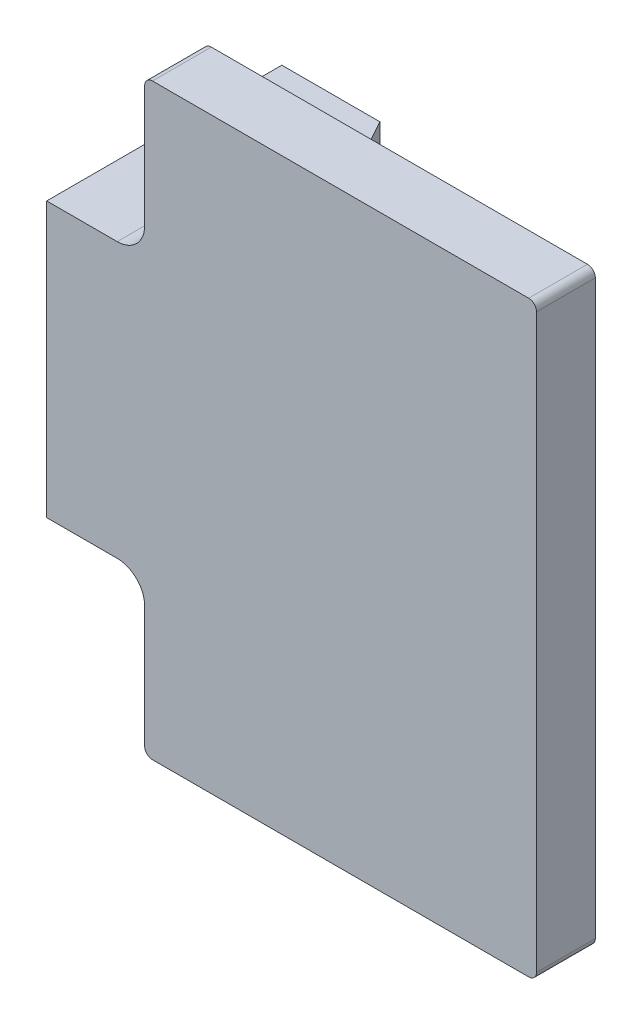
SolidWorks part; units mm, degrees
ref_plane "Plan de face" through (0, 0, 0) normal (0, 0, 1) x (1, 0, 0)
ref_plane "Plan de dessus" through (0, 0, 0) normal (0, 1, 0) x (1, 0, 0)
ref_plane "Plan de droite" through (0, 0, 0) normal (1, 0, 0) x (0, 0, -1)
sketch "Esquisse1" plane through (0, 0, 0) normal (0, 0, 1) x (1, 0, 0)
  line L1 (0, 75) -> (100, 75)
  line L2 (0, 75) -> (0, -75)
  line L3 (0, -75) -> (100, -75)
  line L4 (100, 75) -> (100, -75)
  point P4 (0, 0)
  dimension "D1" = 100
  dimension "D2" = 150
extrude "Boss.-Extru.1" add sketch "Esquisse1" along normal blind 15
sketch "Esquisse2" plane through (0, 0, 15) normal (0, 0, 1) x (1, 0, 0)
  line L0 (0, 75) -> (0, -75) construction
  line L1 (0, 35) -> (-25, 35)
  line L2 (0, 35) -> (0, -35)
  line L3 (0, -35) -> (-25, -35)
  line L4 (-25, 35) -> (-25, -35)
  point P6 (-25, 0)
  dimension "D1" = 70
  dimension "D2" = 25
extrude "Boss.-Extru.2" add sketch "Esquisse2" against normal blind 60
sketch3d "Esquisse3D1"
  line L0 (-25, -35, 5) -> (-25, 35, -45) construction
  line L1 (-25, 35, 5) -> (-25, -35, -45) construction
  line L2 (-25, 0, -20) -> (-55.4382, 0, -20) construction
  line L3 (-25, -35, -45) -> (-25, -35, 15) construction
  line L4 (-25, 35, 15) -> (-25, -35, 15) construction
  dimension "D1" = 10
sketch "Esquisse4" plane through (-25, 0, 0) normal (-1, 0, 0) x (0, 0, 1)
  line L0 (-33.7, 4) -> (-20.2188, 4) construction
  line L1 (-20.2188, -4) -> (-33.7, -4) construction
  line L2 (-33.7, 4) -> (-20.2188, 4) construction
  line L3 (-20.2188, -4) -> (-33.7, -4) construction
  line L4 (-2.2, 0) -> (-2.2, 6.5)
  line L5 (-3.2, 7.5) -> (-9.7, 7.5)
  line L6 (-9.7, -7.5) -> (-15.9939, -7.5)
  line L7 (-16.9939, -6.5) -> (-16.9939, -4.609)
  line L8 (-20.2188, -4.1) -> (-33.7, -4.1)
  line L9 (-33.7, 4.1) -> (-20.2188, 4.1)
  circle A0 centre (-9.7, 0) radius 7.4 construction
  arc A1 (-20.2188, 4) -> (-14.0313, 6) centre (-20.2188, 14.5714) ccw construction
  arc A2 (-14.0313, -6) -> (-20.2188, -4) centre (-20.2188, -14.5714) ccw construction
  arc A3 (-33.7, 4) -> (-37.7, 0) centre (-33.7, 0) ccw construction
  arc A4 (-37.7, 0) -> (-33.7, -4) centre (-33.7, 0) ccw construction
  arc A5 (-14.0313, -6) -> (-14.0313, 6) centre (-9.7, 0) ccw construction
  arc A6 (-20.2188, 4) -> (-14.0313, 6) centre (-20.2188, 14.5714) ccw construction
  arc A7 (-14.0313, -6) -> (-20.2188, -4) centre (-20.2188, -14.5714) ccw construction
  arc A8 (-33.7, 4) -> (-37.7, 0) centre (-33.7, 0) ccw construction
  arc A9 (-37.7, 0) -> (-33.7, -4) centre (-33.7, 0) ccw construction
  arc A10 (-37.8, 0) -> (-33.7, -4.1) centre (-33.7, 0) ccw
  arc A11 (-33.7, 4.1) -> (-37.8, 0) centre (-33.7, 0) ccw
  arc A12 (-20.2188, 4.1) -> (-14.0898, 6.0811) centre (-20.2188, 14.5714) ccw
  arc A13 (-9.7, -7.5) -> (-2.2, 0) centre (-9.7, 0) ccw
  arc A14 (-16.9939, -4.609) -> (-20.2188, -4.1) centre (-20.2188, -14.5714) ccw
  arc A15 (-9.7, 7.5) -> (-14.0898, 6.0811) centre (-9.7, 0) ccw
  arc A16 (-14.0898, -6.0811) -> (-14.0898, 6.0811) centre (-9.7, 0) ccw construction
  arc A17 (-2.2, 6.5) -> (-3.2, 7.5) centre (-3.2, 6.5) ccw
  arc A18 (-14.0898, -6.0811) -> (-20.2188, -4.1) centre (-20.2188, -14.5714) ccw construction
  arc A19 (-15.9939, -7.5) -> (-16.9939, -6.5) centre (-15.9939, -6.5) cw
  dimension "D2" = 1
  dimension "D3" = 0.1
  dimension "D4" = 1
  dimension "D1" = 0.1
extrude "Enlèv. mat.-Extru.1" cut sketch "Esquisse4" against normal blind 4.15
sketch "Esquisse6" plane through (-20.85, 0, 0) normal (-1, 0, 0) x (0, 0, 1)
  line L2 (-29.7, 3) -> (-33.7, 3)
  line L3 (-33.7, -3) -> (-29.7, -3)
  line L12 (-29.7, 3) -> (-33.7, 3) construction
  line L13 (-33.7, -3) -> (-29.7, -3) construction
  circle A0 centre (-33.7, 0) radius 1.75
  arc A1 (-32.45, 0) -> (-34.95, 0) centre (-33.7, 0) ccw construction
  circle A2 centre (-9.7, 0) radius 2.05
  arc A3 (-33.7, 3) -> (-36.7, 0) centre (-33.7, 0) ccw
  arc A4 (-36.7, 0) -> (-33.7, -3) centre (-33.7, 0) ccw
  arc A5 (-29.7, -3) -> (-29.7, 3) centre (-29.7, 0) ccw
  arc A6 (-33.7, 3) -> (-36.7, 0) centre (-33.7, 0) ccw construction
  arc A7 (-36.7, 0) -> (-33.7, -3) centre (-33.7, 0) ccw construction
  arc A8 (-29.7, -3) -> (-29.7, 3) centre (-29.7, 0) ccw construction
  arc A9 (-8.1793, 0.3) -> (-11.2207, 0.3) centre (-9.7, 0) ccw construction
  dimension "D3" = 0.5
  dimension "D4" = 0.5
  dimension "D2" = 0
hole_wizard "Chambrage pour vis à tête ronde bombée M32" positions "Esquisse3D3" profile "Esquisse9" counterbore size "M3" standard "Ansi Metric" end condition up to next
sketch3d "Esquisse3D3"
  point P0 (0, 0, -33.7)
  point P2 (0, 0, -9.7)
sketch "Esquisse9" plane through (0, 0, -33.7) normal (0, 1, 0) x (0, 0, -1)
  line L0 (0, 0) -> (0, 20.85)
  line L1 (0, 20.85) -> (1.7, 20.85)
  line L3 (1.7, 20.85) -> (1.7, 2.4)
  line L4 (1.7, 2.4) -> (3.5, 2.4)
  line L5 (3.5, 2.4) -> (3.5, 0)
  line L7 (3.5, 0) -> (0, 0)
  line L11 (0, -6.35) -> (0, 107.95) construction
  dimension "Diamètre du perçage jusqu'au prochain" = 3.4
  dimension "Profondeur du perçage jusqu'au prochain" = 20.85
  dimension "Diamètre du chambrage" = 7
  dimension "Profondeur du chambrage" = 2.4
sketch "Esquisse10" plane through (0, -35, 0) normal (0, -1, 0) x (1, 0, 0)
  line L0 (0, -45) -> (25, 0)
  line L1 (0, 0) -> (100, 0) construction
  line L2 (25, 0) -> (0, 0)
  line L3 (0, 0) -> (0, -45)
  dimension "D1" = 25
extrude "Boss.-Extru.3" add sketch "Esquisse10" against normal blind 10
mirror "Symétrie1" about plane through (0, 0, 0) normal (0, 1, 0) of "Boss.-Extru.3"
fillet "Congé1" radius 7 2 edges at (0, -35, 7.5) (0, 35, 7.5)
fillet "Congé2" radius 2 5 edges at (0, 0, 0) (100, -75, 7.5) (100, 75, 7.5) (0, -75, 7.5) (0, 75, 7.5)
